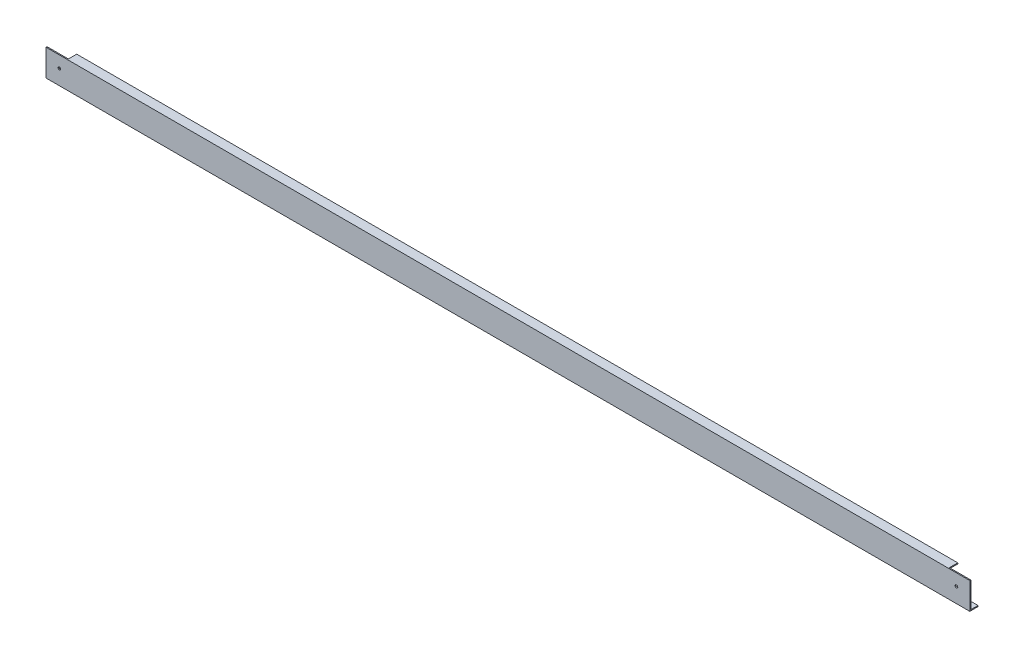
SolidWorks part; units mm, degrees
ref_plane "Front Plane" through (0, 0, 0) normal (0, 0, 1) x (1, 0, 0)
ref_plane "Top Plane" through (0, 0, 0) normal (0, 1, 0) x (1, 0, 0)
ref_plane "Right Plane" through (0, 0, 0) normal (1, 0, 0) x (0, 0, -1)
sketch "Sketch1" plane through (0, 0, 0) normal (1, 0, 0) x (0, 0, -1)
  line L0 (0, 0) -> (0, 127)
  line L1 (0, 127) -> (44.45, 127)
  line L2 (0, 0) -> (39.0507, 0)
  line L3 (4.826, 4.826) -> (39.0507, 4.826)
  line L4 (4.826, 4.826) -> (4.826, 122.174)
  line L5 (4.826, 122.174) -> (44.45, 122.174)
  line L6 (44.45, 127) -> (44.45, 122.174)
  line L7 (39.0507, 4.826) -> (39.0507, 0)
  dimension "D1" = 122.174
  dimension "D2" = 44.45
  dimension "D3" = 4.826
extrude "Boss-Extrude1" add sketch "Sketch1" along normal blind 4394.2
sketch "Sketch2" plane through (0, 0, -4.826) normal (0, 0, -1) x (-1, 0, 0)
  line L0 (-4394.2, 127) -> (0, 127) construction
  line L1 (-4394.2, 4.826) -> (-4394.2, 122.174) construction
  line L2 (0, 4.826) -> (0, 122.174) construction
  circle A0 centre (-4330.7, 71.12) radius 6.35
  circle A1 centre (-63.5, 71.12) radius 6.35
  dimension "D1" = 12.7
  dimension "D4" = 12.7
  dimension "D2" = 55.88
  dimension "D3" = 63.5
  dimension "D5" = 55.88
  dimension "D6" = 63.5
extrude "Cut-Extrude1" cut sketch "Sketch2" against normal up to next
sketch "Sketch3" plane through (0, 0, -4.826) normal (0, 0, -1) x (-1, 0, 0)
  line L19 (-4394.2, 122.174) -> (0, 122.174) construction
  line L20 (-4394.2, 127) -> (-4292.6, 127)
  line L21 (-4394.2, 127) -> (-4394.2, 122.174)
  line L22 (-4394.2, 122.174) -> (-4292.6, 122.174)
  line L23 (-4292.6, 127) -> (-4292.6, 122.174)
  line L25 (0, 127) -> (-101.6, 127)
  line L26 (0, 127) -> (0, 122.174)
  line L27 (0, 122.174) -> (-101.6, 122.174)
  line L28 (-101.6, 127) -> (-101.6, 122.174)
  dimension "D1" = 101.6
  dimension "D2" = 101.6
extrude "Cut-Extrude4" cut sketch "Sketch3" along normal up to next
